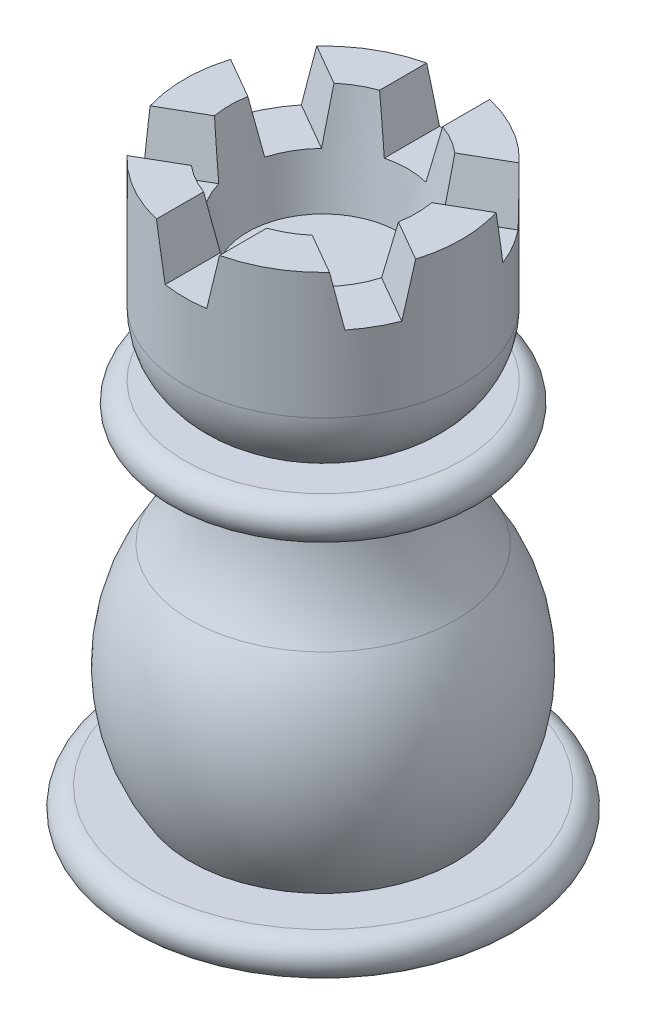
SolidWorks part; units mm, degrees
ref_plane "Front Plane" through (0, 0, 0) normal (0, 0, 1) x (1, 0, 0)
ref_plane "Top Plane" through (0, 0, 0) normal (0, 1, 0) x (1, 0, 0)
ref_plane "Right Plane" through (0, 0, 0) normal (1, 0, 0) x (0, 0, -1)
sketch "Sketch1" plane through (0, 0, 0) normal (0, 0, 1) x (1, 0, 0)
  line L0 (0, 0) -> (0, 43.5943) construction
  line L1 (0, 0) -> (14, 0)
  line L2 (14, 3) -> (10.5, 3)
  line L3 (13, 32.9022) -> (13, 5.1199) construction
  line L4 (8, 27.8038) -> (11, 27.8038)
  line L5 (11, 30.8038) -> (8, 30.8038)
  line L6 (11, 36) -> (11, 46)
  line L7 (11, 46) -> (7.4106, 46)
  line L8 (7.4106, 46) -> (6, 38)
  line L9 (6, 38) -> (0, 38)
  line L10 (0, 38) -> (0, 0)
  arc A0 (14, 0) -> (14, 3) centre (14, 1.5) ccw
  arc A1 (10.5, 3) -> (10.4999, 19.5833) centre (-2, 11.2916) ccw
  arc A2 (10.4999, 19.5833) -> (8, 27.8038) centre (22.9998, 27.8749) cw
  arc A3 (11, 27.8038) -> (11, 30.8038) centre (11, 29.3038) ccw
  arc A4 (8, 30.8038) -> (11, 36) centre (5, 36) ccw
  dimension "D2" = 1.5
  dimension "D3" = 15
  dimension "D4" = 15
  dimension "D8" = 1.5
  dimension "D10" = 6
  dimension "D1" = 14
  dimension "D5" = 10.5
  dimension "D6" = 13
  dimension "D7" = 8
  dimension "D9" = 11
  dimension "D11" = 2
  dimension "D12" = 6
  dimension "D13" = 10
  dimension "D14" = 8
  dimension "D15" = 46
  dimension "D16" = 22
revolve "Revolve1" add sketch "Sketch1" angle 360 about L0
sketch "Sketch2" plane through (0, 0, 0) normal (0, 0, 1) x (1, 0, 0)
  line L0 (0, 52.5735) -> (0, 40.8158) construction
  line L1 (2.5, 46) -> (1.6498, 42)
  line L2 (7.4106, 46) -> (-7.4106, 46) construction
  line L3 (1.6498, 42) -> (-1.6498, 42)
  line L4 (2.5, 46) -> (-2.5, 46)
  line L5 (0, 46) -> (0, 42)
  line L6 (-2.5, 46) -> (-1.6498, 42)
  dimension "D1" = 5
  dimension "D2" = 4
  dimension "D3" = 12
extrude "Cut-Extrude1" cut sketch "Sketch2" against normal through all contours L4 L5 L3 L1 | L4 L6 L3 L5
pattern_circular "CirPattern1" count 6 over 360 about axis through (0, 0, 0) along (0, 1, 0) of "Cut-Extrude1"
